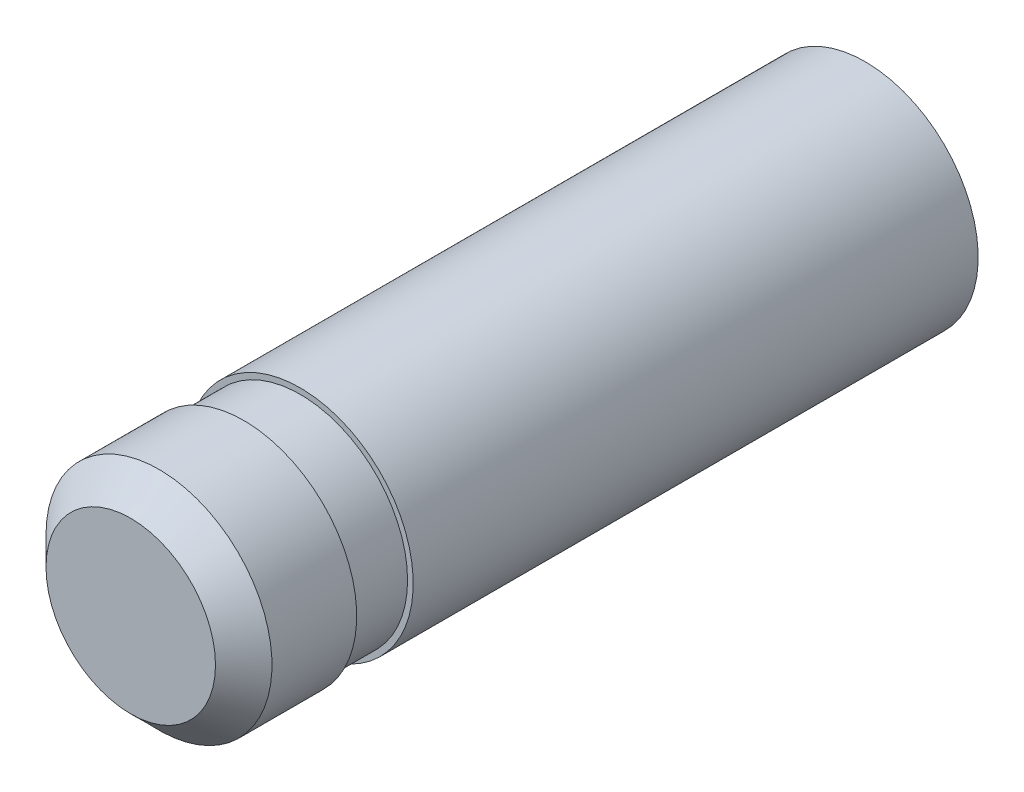
SolidWorks part; units mm, degrees
ref_plane "Front Plane" through (0, 0, 0) normal (0, 0, 1) x (1, 0, 0)
ref_plane "Top Plane" through (0, 0, 0) normal (0, 1, 0) x (1, 0, 0)
ref_plane "Right Plane" through (0, 0, 0) normal (1, 0, 0) x (0, 0, -1)
sketch "Sketch1" plane through (0, 0, 0) normal (0, 0, 1) x (1, 0, 0)
  circle A0 centre (0, 0) radius 2
  dimension "D1" = 4
extrude "Boss-Extrude1" add sketch "Sketch1" along normal mid plane 13
sketch "Sketch2" plane through (0, 0, 6.5) normal (0, 0, 1) x (1, 0, 0)
  circle A0 centre (0, 0) radius 1.9
  circle A1 centre (0, 0) radius 2 construction
  circle A2 centre (0, 0) radius 2
  dimension "D1" = 3.8
extrude "Cut-Extrude1" cut sketch "Sketch2" against normal blind 1 from offset 2 offset against normal yes
chamfer "Chamfer1" distance 0.5 angle 45 1 edges at (2, 0, 6.5)
